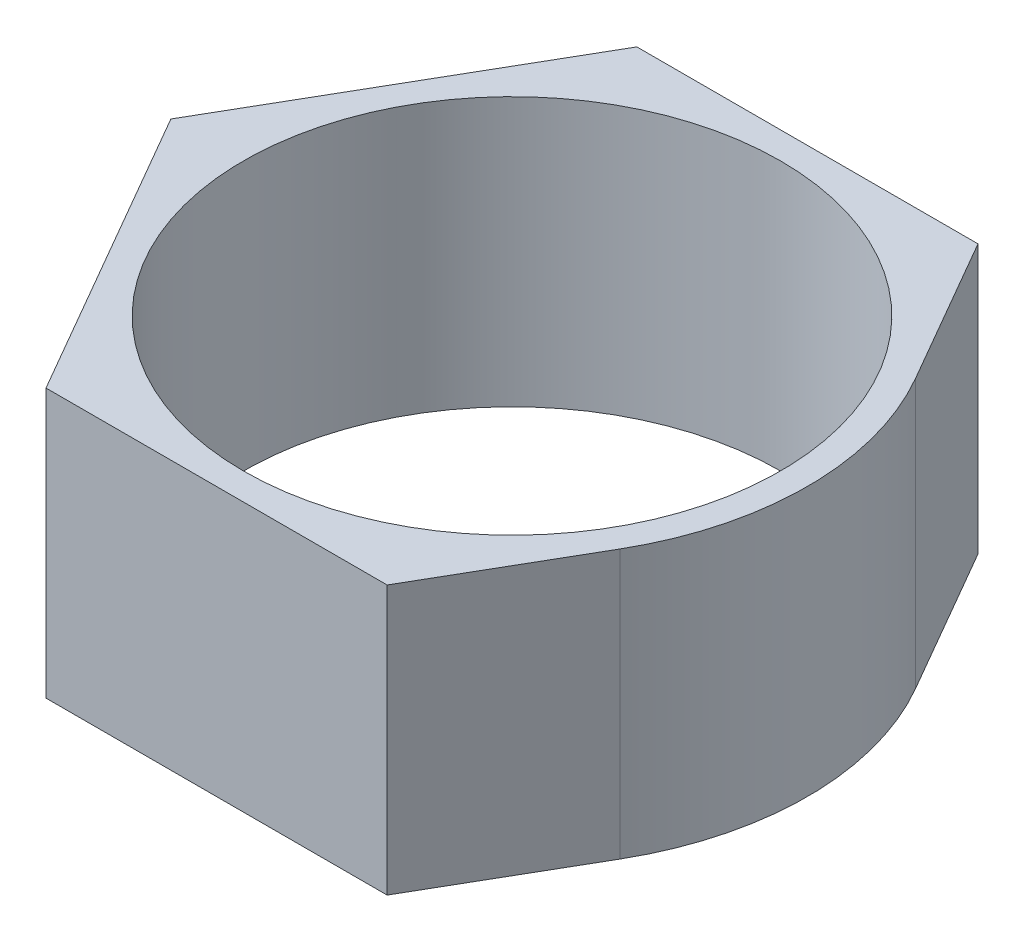
SolidWorks part; units mm, degrees
ref_plane "Front Plane" through (0, 0, 0) normal (0, 0, 1) x (1, 0, 0)
ref_plane "Top Plane" through (0, 0, 0) normal (0, 1, 0) x (1, 0, 0)
ref_plane "Right Plane" through (0, 0, 0) normal (1, 0, 0) x (0, 0, -1)
sketch "Sketch1" plane through (0, 0, 0) normal (0, 1, 0) x (1, 0, 0)
  line L1 (9.5263, 5.5) -> (6.3509, 11)
  line L2 (6.3509, 11) -> (-6.3509, 11)
  line L3 (-6.3509, 11) -> (-12.7017, 0)
  line L4 (-12.7017, 0) -> (-6.3509, -11)
  line L5 (-6.3509, -11) -> (6.3509, -11)
  line L6 (6.3509, -11) -> (9.5263, -5.5)
  circle A0 centre (0, 0) radius 10
  circle A1 centre (0, 0) radius 11 construction
  circle A2 centre (0, 0) radius 11
  point P13 (0, 0)
  dimension "D1" = 11
  dimension "D2" = 11
extrude "Boss-Extrude3" add sketch "Sketch1" along normal blind 10 contours A2 A0 | A2 L3 L4 | A2 L4 L5 | A2 L5 L6 | A2 L1 L2 | A2 L2 L3
